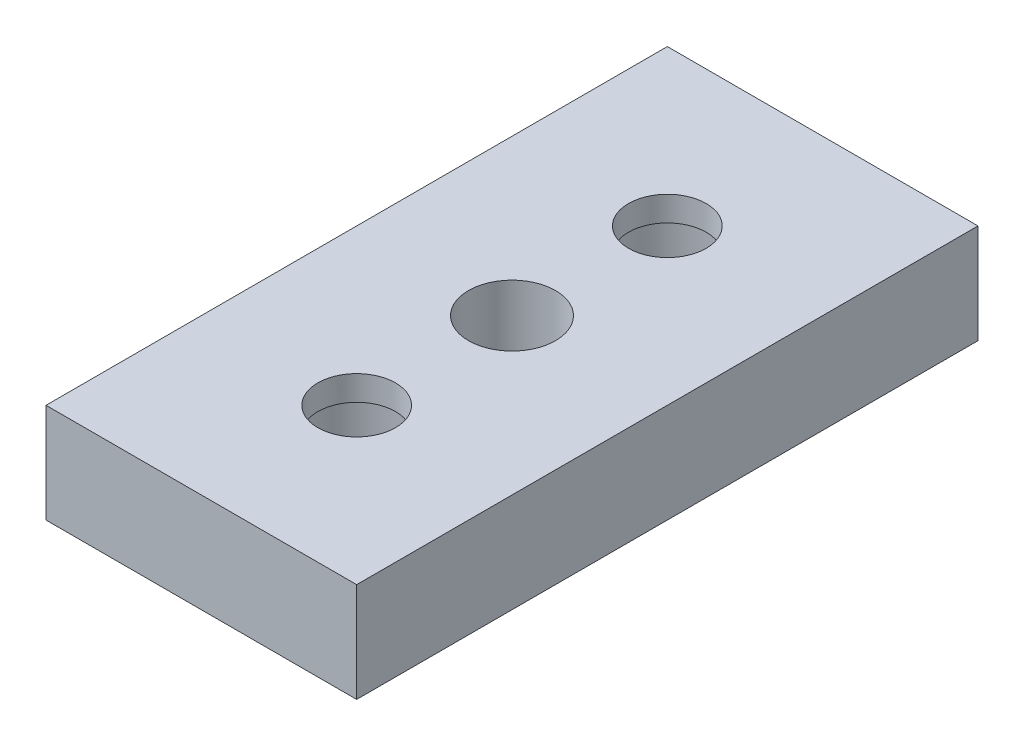
SolidWorks part; units mm, degrees
ref_plane "前视基准面" through (0, 0, 0) normal (0, 0, 1) x (1, 0, 0)
ref_plane "上视基准面" through (0, 0, 0) normal (0, 1, 0) x (1, 0, 0)
ref_plane "右视基准面" through (0, 0, 0) normal (1, 0, 0) x (0, 0, -1)
sketch "草图1" plane through (0, 0, 0) normal (0, 1, 0) x (1, 0, 0)
  line B0 (0, 0) -> (50, 0)
  line B1 (50, 0) -> (50, 100)
  line B2 (50, 100) -> (0, 100)
  line B3 (0, 100) -> (0, 0)
  circle B4 centre (25, 75) radius 6.25
  circle B5 centre (25, 25) radius 6.25
sketch_block_instance "A$C21CF577E-1"
sketch_block "A$C21CF577E"
extrude "凸台-拉伸1" add sketch "草图1" along normal blind 16
sketch "草图3" plane through (0, 16, 0) normal (0, 1, 0) x (1, 0, 0)
  point P0 (25, 50)
hole_wizard "M16 螺纹孔1" positions "3D草图1" profile "草图4" tap size "M16" standard "Iso"
sketch3d "3D草图1"
  point P0 (25, 16, -50)
sketch "草图4" plane through (25, 16, -50) normal (1, 0, 0) x (0, 0, 1)
  line L0 (0, 0) -> (0, 42.206)
  line L1 (0, 42.206) -> (7, 38)
  line L2 (7, 38) -> (7, 0)
  line L5 (7, 0) -> (0, 0)
  line L10 (0, 42.206) -> (-7, 38) construction
  line L11 (0, -6.35) -> (0, 107.95) construction
  dimension "螺纹孔钻头直径" = 14
  dimension "螺纹孔钻头深度" = 38
  dimension "导头角度" = 118
cosmetic thread "孔螺蚊线1" parameters "D1"=16, "D2"=16
sketch "草图5" plane through (0, 0, 0) normal (0, -1, 0) x (1, 0, 0)
  circle A0 centre (25, -25) radius 9.25
  circle A1 centre (25, -75) radius 9.25
extrude "切除-拉伸1" cut sketch "草图5" against normal blind 12
